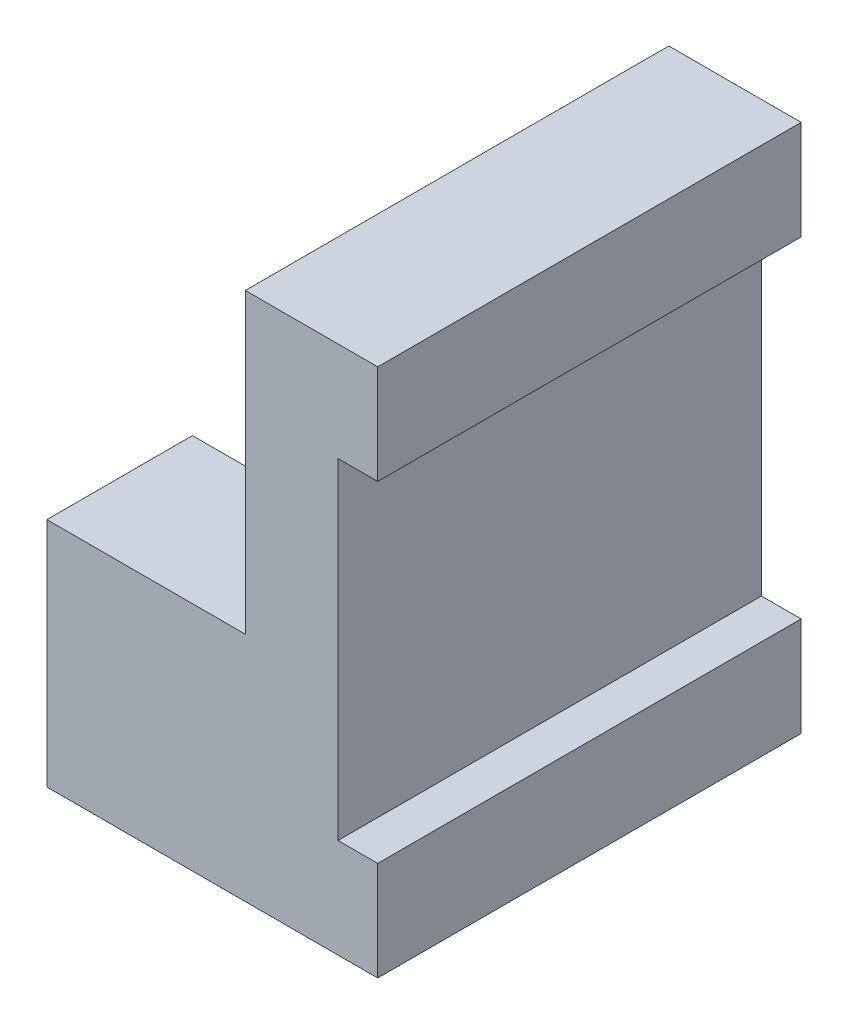
SolidWorks part; units mm, degrees
ref_plane "Front Plane" through (0, 0, 0) normal (0, 0, 1) x (1, 0, 0)
ref_plane "Top Plane" through (0, 0, 0) normal (0, 1, 0) x (1, 0, 0)
ref_plane "Right Plane" through (0, 0, 0) normal (1, 0, 0) x (0, 0, -1)
sketch "Sketch2" plane through (0, 0, 0) normal (0, 0, 1) x (1, 0, 0)
  line L0 (0, 0) -> (50, 0)
  line L1 (0, 0) -> (0, 35)
  line L2 (0, 35) -> (30, 35)
  line L3 (30, 35) -> (30, 80)
  line L4 (30, 80) -> (50, 80)
  line L5 (50, 80) -> (50, 65)
  line L6 (50, 65) -> (44, 65)
  line L7 (44, 65) -> (44, 15)
  line L8 (44, 15) -> (50, 15)
  line L9 (50, 15) -> (50, 0)
extrude "Boss-Extrude1" add sketch "Sketch2" along normal blind 64
sketch "Sketch4" plane through (0, 0, 0) normal (-1, 0, 0) x (0, 0, 1)
  line L0 (64, 0) -> (0, 0) construction
  line L1 (22, 0) -> (42, 0)
  line L2 (22, 0) -> (22, 35)
  line L3 (22, 35) -> (42, 35)
  line L4 (42, 0) -> (42, 35)
  line L5 (64, 35) -> (0, 35) construction
  line L6 (0, 35) -> (0, 0) construction
  line L7 (64, 35) -> (64, 0) construction
  dimension "D1" = 22
  dimension "D2" = 22
extrude "Cut-Extrude2" cut sketch "Sketch4" against normal blind 22
